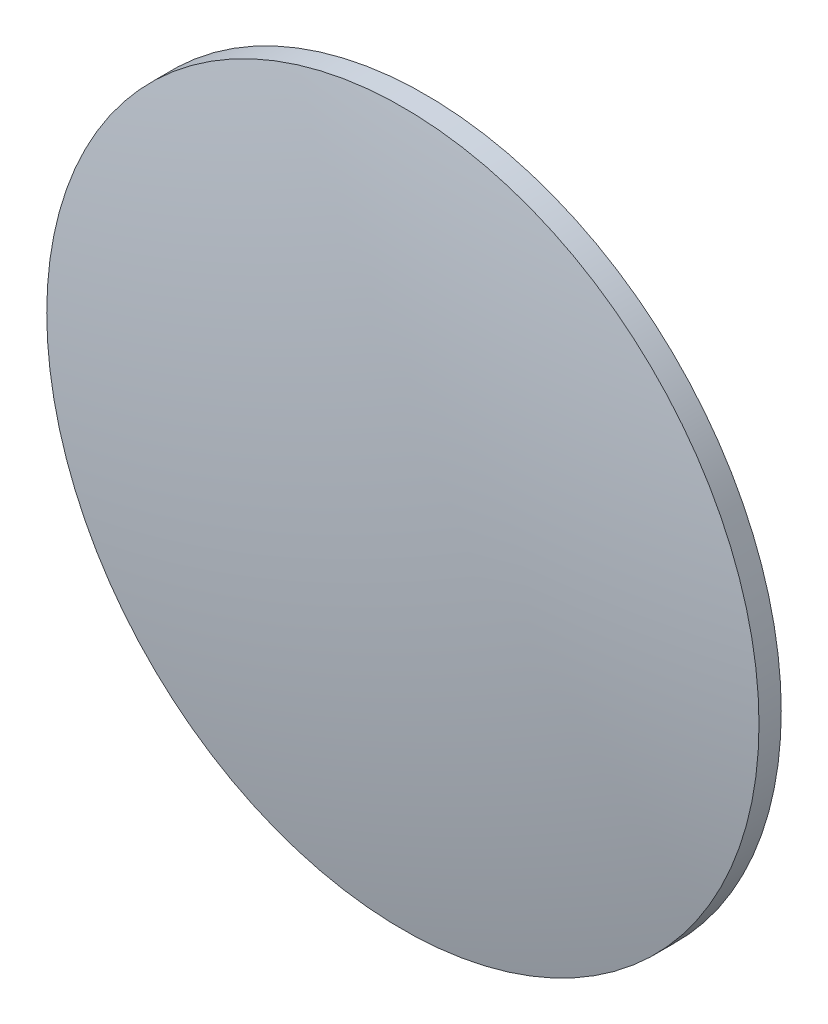
SolidWorks part; units mm, degrees
ref_plane "Front Plane" through (0, 0, 0) normal (0, 0, 1) x (1, 0, 0)
ref_plane "Top Plane" through (0, 0, 0) normal (0, 1, 0) x (1, 0, 0)
ref_plane "Right Plane" through (0, 0, 0) normal (1, 0, 0) x (0, 0, -1)
sketch "Sketch2" plane through (0, 0, 0) normal (0, 1, 0) x (1, 0, 0)
  line L0 (0, 0) -> (50.8, 0)
  line L1 (0, -6.35) -> (0, 6.35)
  line L2 (50.8, -1.5875) -> (50.8, 1.5875)
  line L3 (0, 6.35) -> (4.9997, 6.35)
  arc A0 (0, 6.35) -> (50.8, 1.5875) centre (0, -266.9646) cw
  arc A1 (0, -6.35) -> (50.8, -1.5875) centre (0, 266.9646) ccw
  point P6 (0, 0)
  point P9 (50.8, 0)
  dimension "D1" = 50.8
  dimension "D2" = 6.35
  dimension "D3" = 1.5875
revolve "Revolve1" add sketch "Sketch2" angle 360 about L1
